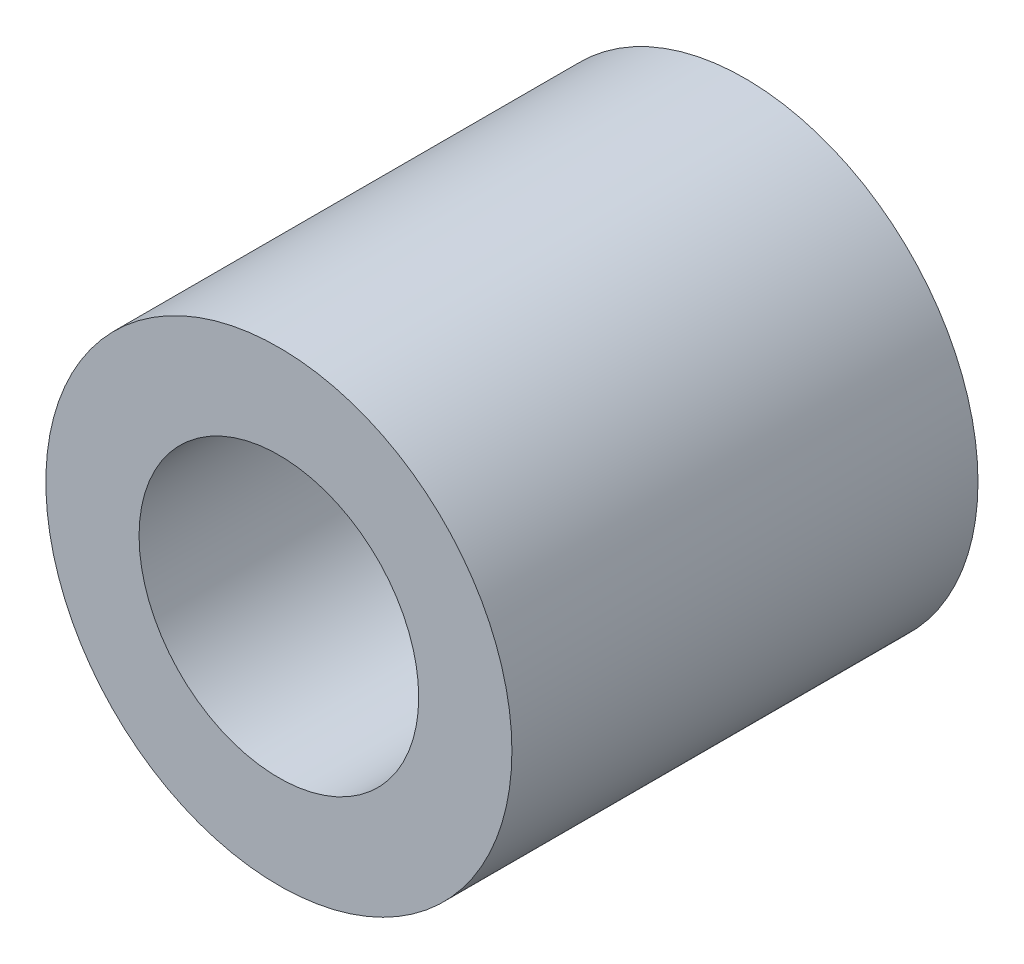
SolidWorks part; units mm, degrees
ref_plane "Alzado" through (0, 0, 0) normal (0, 0, 1) x (1, 0, 0)
ref_plane "Planta" through (0, 0, 0) normal (0, 1, 0) x (1, 0, 0)
ref_plane "Vista lateral" through (0, 0, 0) normal (1, 0, 0) x (0, 0, -1)
sketch "Croquis1" plane through (0, 0, 0) normal (0, 0, 1) x (1, 0, 0)
  circle A0 centre (0, 0) radius 2.5
  dimension "D1" = 5
extrude "Saliente-Extruir1" add sketch "Croquis1" along normal blind 5
sketch "Croquis2" plane through (0, 0, 5) normal (0, 0, 1) x (1, 0, 0)
  circle A0 centre (0, 0) radius 1.5
  dimension "D1" = 3
extrude "Cortar-Extruir1" cut sketch "Croquis2" against normal up to next
